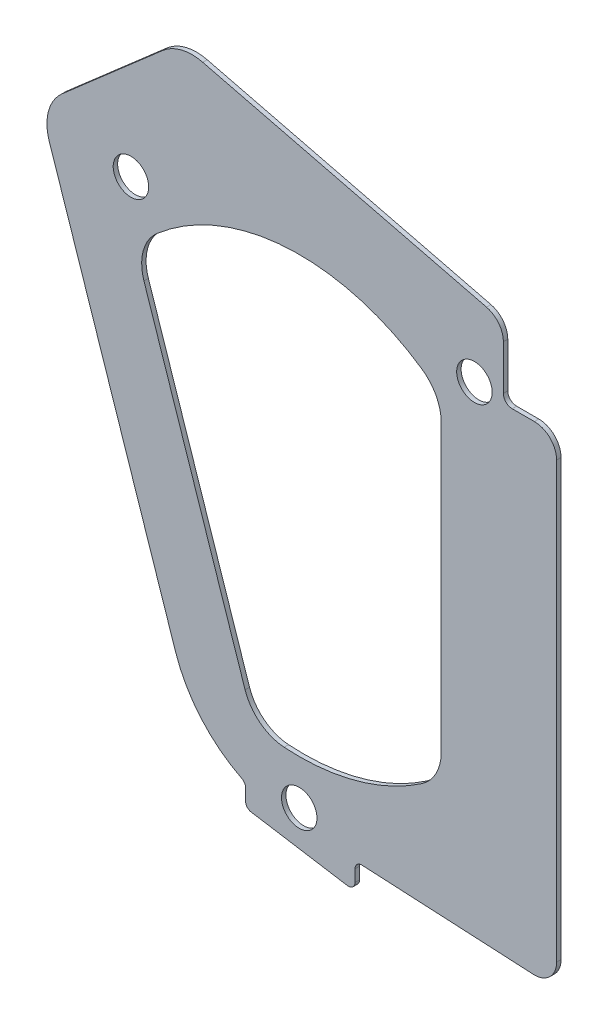
SolidWorks part; units mm, degrees
ref_plane "Front Plane" through (0, 0, 0) normal (0, 0, 1) x (1, 0, 0)
ref_plane "Top Plane" through (0, 0, 0) normal (0, 1, 0) x (1, 0, 0)
ref_plane "Right Plane" through (0, 0, 0) normal (1, 0, 0) x (0, 0, -1)
sketch "Sketch1" plane through (0, 0, 0) normal (0, 0, 1) x (1, 0, 0)
  line L0 (-37.9245, 45.1966) -> (0, 0) construction
  line L1 (0, 0) -> (0, 59) construction
  line L4 (32, 32.2025) -> (32, -32.2025)
  line L5 (-12.099, -61.1049) -> (-12.099, -63.7625)
  line L6 (-10.839, -65.2431) -> (10.839, -68.7569)
  line L7 (12.579, -67.2762) -> (12.579, -64.6187)
  line L8 (14.1566, -63.1207) -> (52.7412, -65.1207)
  line L9 (58, -60.1274) -> (58, 37.8793)
  line L10 (53, 42.8793) -> (48, 42.8793)
  line L11 (46, 44.8793) -> (46, 54.9649)
  line L12 (42.2, 59.8188) -> (-21.7544, 75.63)
  line L14 (-12.099, -60.1656) -> (-9.38, -61.4334) construction
  line L15 (-30.73, 73.4563) -> (-53.4342, 53.6407)
  line L16 (-56.3457, 42.9448) -> (-27.8814, -42.4618)
  line L17 (-34.9992, 26.3361) -> (-12.2017, -42.0672)
  line L18 (39.4787, 43.8455) -> (0, 0) construction
  circle A0 centre (0, 0) radius 59 construction
  arc A2 (27.641, 40.4595) -> (-32.0538, 37.0615) centre (0, 0) ccw
  circle A3 centre (0, -59) radius 4
  circle A4 centre (-37.9245, 45.1966) radius 4
  circle A5 centre (39.4787, 43.8455) radius 4
  arc A6 (-27.8814, -42.4618) -> (-12.9238, -59.7655) centre (0.5796, -32.9763) ccw
  circle A7 centre (0, 0) radius 49 construction
  arc A9 (32, -32.2025) -> (27.641, -40.4595) centre (22, -32.2025) cw
  arc A10 (32, 32.2025) -> (27.641, 40.4595) centre (22, 32.2025) ccw
  arc A11 (-3.4108, -48.8811) -> (27.641, -40.4595) centre (0, 0) ccw
  arc A12 (-12.2017, -42.0672) -> (-3.4108, -48.8811) centre (-2.7147, -38.9054) ccw
  arc A13 (-34.9992, 26.3361) -> (-32.0538, 37.0615) centre (-25.5122, 29.4979) cw
  arc A14 (-21.7544, 75.63) -> (-30.73, 73.4563) centre (-24.1544, 65.9222) ccw
  arc A15 (-53.4342, 53.6407) -> (-56.3457, 42.9448) centre (-46.8587, 46.1066) ccw
  arc A16 (58, 37.8793) -> (53, 42.8793) centre (53, 37.8793) ccw
  arc A17 (46, 54.9649) -> (42.2, 59.8188) centre (41, 54.9649) ccw
  arc A18 (48, 42.8793) -> (46, 44.8793) centre (48, 44.8793) cw
  arc A19 (52.7412, -65.1207) -> (58, -60.1274) centre (53, -60.1274) ccw
  arc A20 (12.579, -64.6187) -> (14.1566, -63.1207) centre (14.079, -64.6187) cw
  arc A21 (10.839, -68.7569) -> (12.579, -67.2762) centre (11.079, -67.2762) ccw
  arc A22 (-12.099, -63.7625) -> (-10.839, -65.2431) centre (-10.599, -63.7625) ccw
  arc A23 (-12.099, -61.1049) -> (-12.9238, -59.7655) centre (-13.599, -61.1049) ccw
  point P30 (0, -67)
  point P39 (-10.2527, -47.9154)
  point P44 (-26.808, 76.8793)
  point P47 (-58.4511, 49.2621)
  point P50 (58, 42.8793)
  point P53 (46, 58.8793)
  point P56 (46, 42.8793)
  point P59 (58, -65.3933)
  point P62 (12.579, -63.0389)
  point P65 (12.579, -69.0389)
  point P68 (-12.099, -65.0389)
  dimension "D1" = 118
  dimension "D4" = 8
  dimension "D8" = 58
  dimension "D9" = 10
  dimension "D18" = 30
  dimension "D23" = 10
  dimension "D24" = 10
  dimension "D25" = 5
  dimension "D26" = 2
  dimension "D27" = 5
  dimension "D28" = 1.5
  dimension "D5" = 40
  dimension "D6" = 6
  dimension "D7" = 32
  dimension "D2" = 25
  dimension "D10" = 12
  dimension "D11" = 108
  dimension "D12" = 8
  dimension "D13" = 4
  dimension "D14" = 16
  dimension "D15" = 18
  dimension "D16" = 3
  dimension "D17" = 65
  dimension "D19" = 75
  dimension "D20" = 42
  dimension "D21" = 125
  dimension "D22" = 15
  dimension "D29" = 2
  dimension "D30" = 42
  dimension "D3" = 10
extrude "Bumper link" add sketch "Sketch1" along normal blind 1
